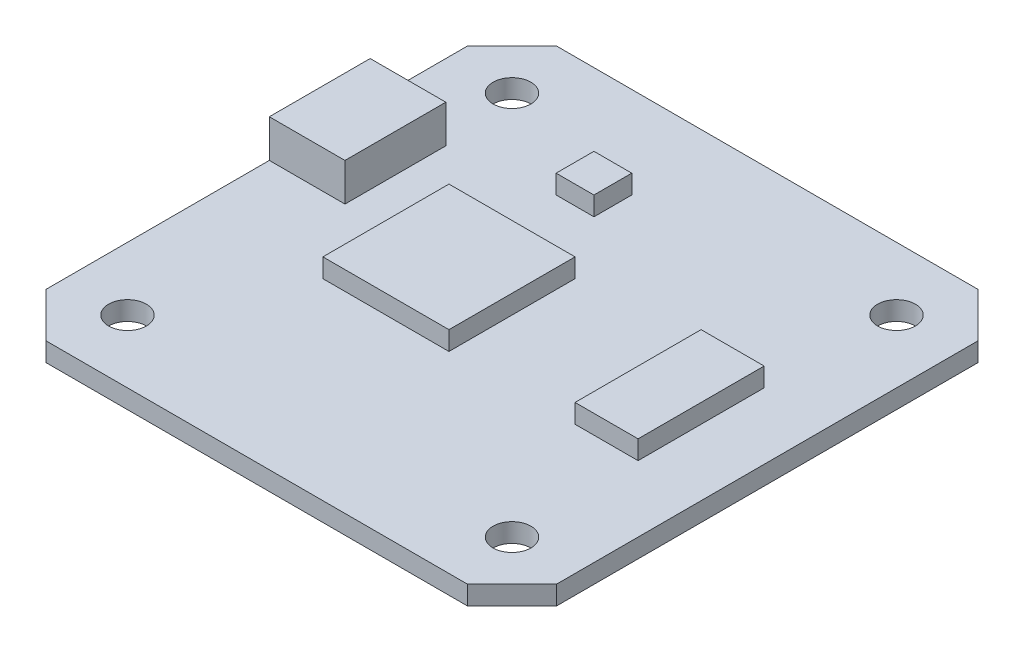
SolidWorks part; units mm, degrees
ref_plane "Front Plane" through (0, 0, 0) normal (0, 0, 1) x (1, 0, 0)
ref_plane "Top Plane" through (0, 0, 0) normal (0, 1, 0) x (1, 0, 0)
ref_plane "Right Plane" through (0, 0, 0) normal (1, 0, 0) x (0, 0, -1)
sketch "Sketch1" plane through (0, 0, 0) normal (0, 1, 0) x (1, 0, 0)
  line L0 (16.7145, 20.25) -> (-16.7145, 20.25)
  line L1 (-16.7145, 20.25) -> (-20.25, 16.7145)
  line L2 (-20.25, 16.7145) -> (-20.25, -16.7145)
  line L3 (-20.25, -16.7145) -> (-16.7145, -20.25)
  line L4 (-16.7145, -20.25) -> (16.7145, -20.25)
  line L5 (0, -20.25) -> (0, 20.25) construction
  line L6 (20.25, -16.7145) -> (16.7145, -20.25)
  line L7 (20.25, 16.7145) -> (20.25, -16.7145)
  line L8 (16.7145, 20.25) -> (20.25, 16.7145)
  circle A0 centre (-15.25, 15.25) radius 1.5
  circle A1 centre (-15.25, -15.25) radius 1.5
  circle A2 centre (15.25, -15.25) radius 1.5
  circle A3 centre (15.25, 15.25) radius 1.5
  point P2 (0, 0)
  point P12 (-70.8426, -45.9481)
  point P13 (0, 0)
  point P14 (-16.9779, 20.25)
  dimension "D4" = 3
  dimension "D1" = 135
  dimension "D2" = 135
  dimension "D3" = 15.25
  dimension "D5" = 15.25
  dimension "D6" = 15.25
  dimension "D7" = 5
  dimension "D8" = 5
  dimension "D9" = 5
extrude "Boss-Extrude1" add sketch "Sketch1" along normal blind 1.5
sketch "Sketch2" plane through (0, 1.5, 0) normal (0, 1, 0) x (1, 0, 0)
  line L1 (-10, 5) -> (0, 5)
  line L2 (-10, 5) -> (-10, -5)
  line L3 (-10, -5) -> (0, -5)
  line L4 (0, 5) -> (0, -5)
  line L5 (10, 5) -> (15, 5)
  line L6 (10, 5) -> (10, -5)
  line L7 (10, -5) -> (15, -5)
  line L8 (15, 5) -> (15, -5)
  line L9 (-6.5, 13) -> (-3.5, 13)
  line L10 (-6.5, 13) -> (-6.5, 10)
  line L11 (-6.5, 10) -> (-3.5, 10)
  line L12 (-3.5, 13) -> (-3.5, 10)
  point P12 (0, 0)
  point P14 (-5, 10)
  point P15 (-5, 5)
  dimension "D1" = 10
  dimension "D2" = 3
  dimension "D3" = 5
  dimension "D4" = 10
  dimension "D5" = 5
  dimension "D6" = 10
extrude "Boss-Extrude2" add sketch "Sketch2" along normal blind 1.5
sketch "Sketch3" plane through (0, 1.5, 0) normal (0, 1, 0) x (1, 0, 0)
  line L0 (-20.25, 16.7145) -> (-20.25, -16.7145) construction
  line L1 (-20.25, 9) -> (-14.25, 9)
  line L2 (-20.25, 9) -> (-20.25, 1)
  line L3 (-20.25, 1) -> (-14.25, 1)
  line L4 (-14.25, 9) -> (-14.25, 1)
  line L5 (0, 5) -> (-10, 5) construction
  dimension "D1" = 8
  dimension "D2" = 6
  dimension "D3" = 4
extrude "Boss-Extrude3" add sketch "Sketch3" along normal blind 3
